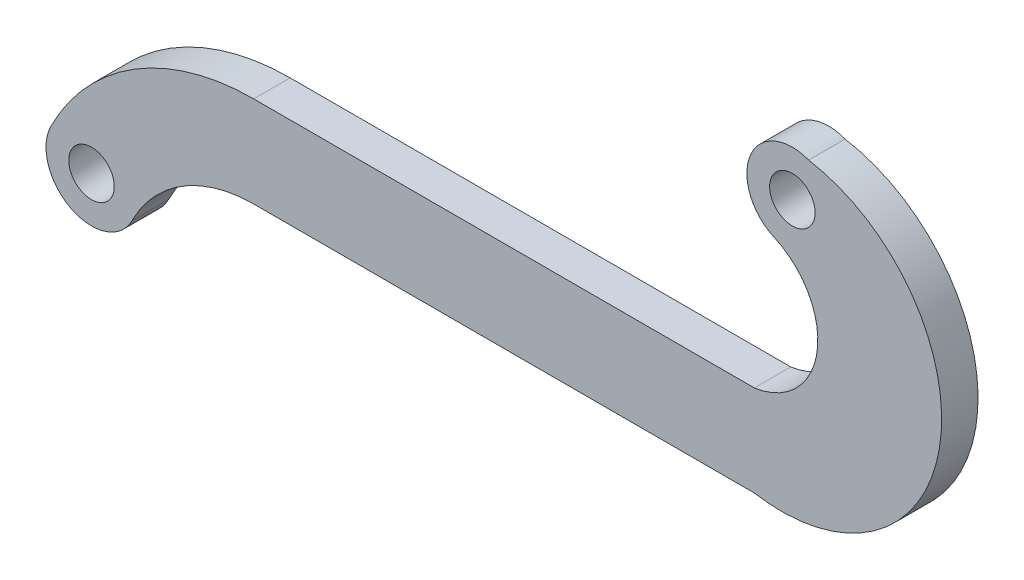
SolidWorks part; units mm, degrees
ref_plane "Front Plane" through (0, 0, 0) normal (0, 0, 1) x (1, 0, 0)
ref_plane "Top Plane" through (0, 0, 0) normal (0, 1, 0) x (1, 0, 0)
ref_plane "Right Plane" through (0, 0, 0) normal (1, 0, 0) x (0, 0, -1)
sketch "Sketch1" plane through (0, 0, 0) normal (0, 0, 1) x (1, 0, 0)
  line L0 (0, 0) -> (22, 0)
  line L1 (22, 4) -> (0, 4)
  arc A1 (24.3925, 13.8654) -> (22.8617, 10.1711) centre (23.671, 12) ccw
  arc A3 (0, 4) -> (-8.9167, -1.5034) centre (0, -5.9752) ccw
  arc A4 (-8.9167, -1.5034) -> (-5.3412, -3.2966) centre (-7.129, -2.4) ccw
  arc A5 (-5.3412, -3.2966) -> (0, 0) centre (0, -5.9752) cw
  circle A6 centre (-7.129, -2.4) radius 1
  circle A7 centre (23.671, 12) radius 1
  arc A8 (22, 4) -> (22.8617, 10.1711) centre (21.5508, 7.2084) ccw
  arc A9 (22, 0) -> (24.3925, 13.8654) centre (23.1962, 6.9327) ccw
  dimension "D2" = 2
  dimension "D3" = 2
  dimension "D4" = 2
  dimension "D6" = 2
  dimension "D10" = 0
  dimension "D1" = 34
  dimension "D5" = 4
  dimension "D7" = 12
  dimension "D8" = 6.4
  dimension "D9" = 22
extrude "Boss-Extrude2" add sketch "Sketch1" along normal blind 1.6
